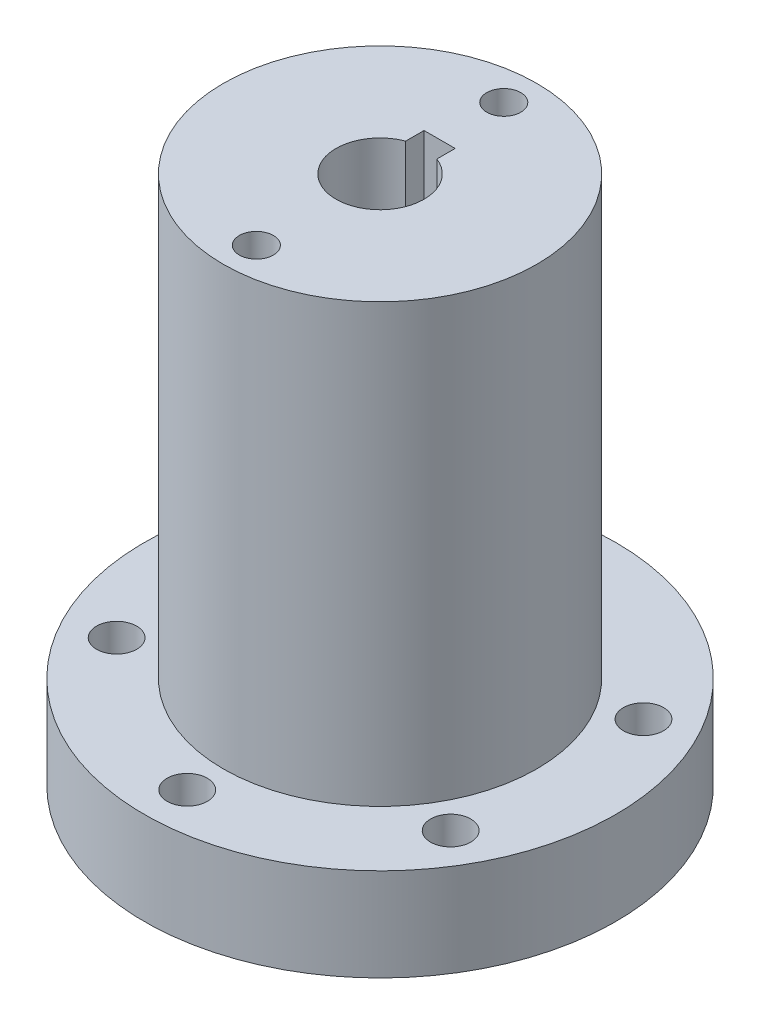
SolidWorks part; units mm, degrees
ref_plane "Front Plane" through (0, 0, 0) normal (0, 0, 1) x (1, 0, 0)
ref_plane "Top Plane" through (0, 0, 0) normal (0, 1, 0) x (1, 0, 0)
ref_plane "Right Plane" through (0, 0, 0) normal (1, 0, 0) x (0, 0, -1)
sketch "Sketch1" plane through (0, 0, 0) normal (0, 1, 0) x (1, 0, 0)
  circle A0 centre (0, 0) radius 25.34
extrude "Boss-Extrude1" add sketch "Sketch1" along normal blind 8.5
sketch "Sketch2" plane through (0, 8.5, 0) normal (0, 1, 0) x (1, 0, 0)
  circle A0 centre (0, 0) radius 25.34
extrude "Boss-Extrude2" add sketch "Sketch2" along normal blind 57.15
sketch "Sketch7" plane through (0, 65.65, 0) normal (0, 1, 0) x (1, 0, 0)
  circle A0 centre (0, 0) radius 25.34
extrude "Boss-Extrude4" add sketch "Sketch7" along normal blind 15
sketch "Sketch5" plane through (0, 0, 0) normal (0, -1, 0) x (1, 0, 0)
  line L1 (-2.575, 9.15) -> (2.575, 9.15)
  line L2 (-2.575, 9.15) -> (-2.575, 4)
  line L3 (-2.575, 4) -> (2.575, 4)
  line L4 (2.575, 9.15) -> (2.575, 4)
  circle A0 centre (0, 0) radius 7.25
  dimension "D1" = 5.15
  dimension "D2" = 5.15
  dimension "D3" = 9.15
  dimension "D4" = 2.575
extrude "Cut-Extrude3" cut sketch "Sketch5" against normal blind 115 contours L2 A0 L4 L3 | L4 A0 L2 L3 | A0 L4 L1 L2
sketch "Sketch6" plane through (0, 0, 0) normal (0, -1, 0) x (1, 0, 0)
  circle A0 centre (0, 0) radius 38.1
extrude "Boss-Extrude3" add sketch "Sketch6" along normal blind 15
sketch "Sketch9" plane through (0, 0, 0) normal (0, 1, 0) x (1, 0, 0)
  line L1 (0, 31.1769) -> (-27, 15.5885)
  line L2 (-27, 15.5885) -> (-27, -15.5885)
  line L3 (-27, -15.5885) -> (0, -31.1769)
  line L4 (0, -31.1769) -> (27, -15.5885)
  line L5 (27, -15.5885) -> (27, 15.5885)
  line L6 (27, 15.5885) -> (0, 31.1769)
  circle A0 centre (0, 0) radius 27 construction
  circle A1 centre (0, 31.1769) radius 3.25
  circle A2 centre (-27, 15.5885) radius 3.25
  circle A3 centre (-27, -15.5885) radius 3.25
  circle A4 centre (0, -31.1769) radius 3.25
  circle A5 centre (27, -15.5885) radius 3.25
  circle A6 centre (27, 15.5885) radius 3.25
extrude "Cut-Extrude4" cut sketch "Sketch9" against normal blind 20 contours L1 A2 L2 | L2 A2 L1 | L6 A1 L1 | L1 A1 L6 | L5 A6 L6 | L6 A6 L5 | L4 A5 L5 | L5 A5 L4 | L3 A4 L4 | L4 A4 L3 | L2 A3 L3 | L3 A3 L2
sketch "Sketch10" plane through (0, 80.65, 0) normal (0, 1, 0) x (1, 0, 0)
  circle A0 centre (0, 20) radius 2.75
  circle A1 centre (0, -20) radius 2.75
  arc A2 (2.575, -6.7773) -> (-2.575, -6.7773) centre (0, 0) ccw construction
  dimension "D1" = 20
  dimension "D2" = 20
extrude "Cut-Extrude6" cut sketch "Sketch10" against normal blind 129
sketch "Sketch11" plane through (0, 80.65, 0) normal (0, 1, 0) x (1, 0, 0)
  line L1 (-2.575, -9.15) -> (2.575, -9.15)
  line L3 (0, -7.12) -> (0, -9.15)
  circle A0 centre (0, 0) radius 7.12
  arc M3 (-2.575, -6.7773) -> (2.575, -6.7773) centre (0, 0) cw
  line M4 (2.575, -6.7773) -> (2.575, -9.15)
  line M5 (2.575, -9.15) -> (-2.575, -9.15)
  line M6 (-2.575, -9.15) -> (-2.575, -6.7773)
  dimension "D1" = 14.24
extrude "Boss-Extrude5" add sketch "Sketch11" against normal blind 93 contours A0 M3 | A0 M6 M5 M4
sketch "Sketch12" plane through (0, 80.65, 0) normal (0, 1, 0) x (1, 0, 0)
  circle A0 centre (0, 0) radius 25.34
extrude "Cut-Extrude8" cut sketch "Sketch12" against normal blind 10
sketch "Sketch13" plane through (0, 70.65, 0) normal (0, 1, 0) x (1, 0, 0)
  line L0 (0, 7.12) -> (2.5148, 7.12)
  line L1 (0, 7.12) -> (-2.5148, 7.12)
  line L2 (-2.5148, 7.12) -> (-2.5148, 9.6264)
  line L3 (-2.5148, 9.6264) -> (2.5148, 9.6264)
  line L4 (2.5148, 9.6264) -> (2.5148, 7.12)
  line L5 (2.5148, 7.12) -> (2.5148, 6.6611)
  line L6 (-2.5148, 7.12) -> (-2.5148, 6.6611)
  circle A0 centre (0, 0) radius 7.12
extrude "Cut-Extrude9" cut sketch "Sketch13" against normal blind 40 contours L4 L3 L2 L1 L0 | A0 | A0 L1 L6 | A0 L5 L0
